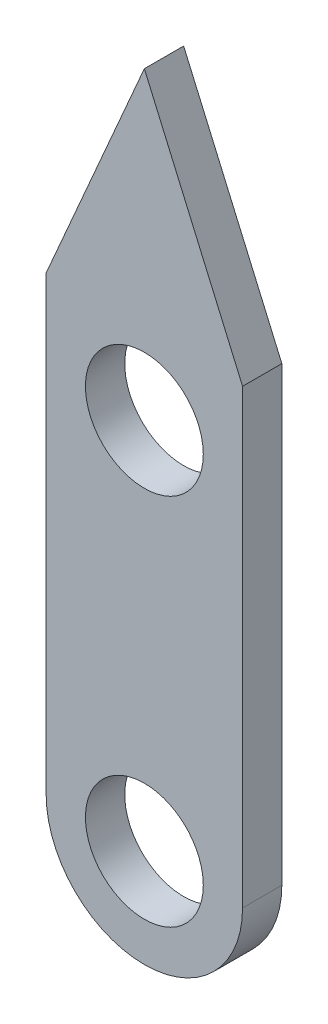
SolidWorks part; units mm, degrees
ref_plane "前视基准面" through (0, 0, 0) normal (0, 0, 1) x (1, 0, 0)
ref_plane "上视基准面" through (0, 0, 0) normal (0, 1, 0) x (1, 0, 0)
ref_plane "右视基准面" through (0, 0, 0) normal (1, 0, 0) x (0, 0, -1)
sketch "草图1" plane through (0, 0, 0) normal (0, 0, 1) x (1, 0, 0)
  line L0 (-0.0558, 9.4466) -> (-0.0558, -9.5534) construction
  line L1 (-0.0558, -0.0534) -> (-2.1366, -0.0534) construction
  line L2 (4.9442, 9.4466) -> (4.9442, -9.5534)
  line L3 (-5.0558, 9.4466) -> (-5.0558, -9.5534)
  line L4 (-5.0558, 9.4466) -> (-5.0558, 13.4466)
  line L5 (4.9442, 9.4466) -> (4.9442, 13.4466)
  line L6 (4.9442, 13.4466) -> (-0.0558, 24.9506)
  line L7 (-0.0558, 24.9506) -> (-5.0558, 13.4466)
  circle A1 centre (-0.0558, 9.4466) radius 3
  circle A2 centre (-0.0558, -9.5534) radius 3
  arc A4 (4.9442, -9.5534) -> (-5.0558, -9.5534) centre (-0.0558, -9.5534) cw
extrude "凸台-拉伸1" add sketch "草图1" along normal blind 2
